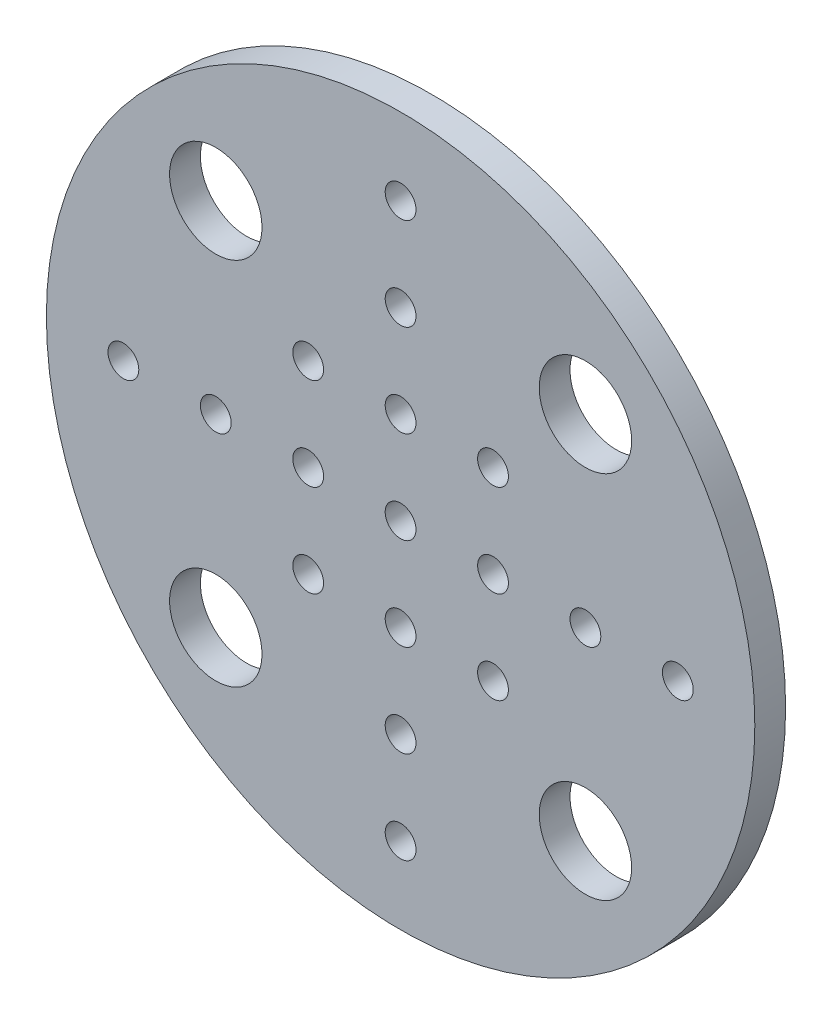
SolidWorks part; units mm, degrees
ref_plane "Alzado" through (0, 0, 0) normal (0, 0, 1) x (1, 0, 0)
ref_plane "Planta" through (0, 0, 0) normal (0, 1, 0) x (1, 0, 0)
ref_plane "Vista lateral" through (0, 0, 0) normal (1, 0, 0) x (0, 0, -1)
sketch "Model" plane through (0, 0, 0) normal (0, 0, 1) x (1, 0, 0)
  circle A0 centre (281.5188, 303.8788) radius 4.5
  circle A1 centre (281.5188, 267.8788) radius 4.5
  circle A2 centre (317.5188, 267.8788) radius 4.5
  circle A3 centre (317.5188, 303.8788) radius 4.5
  circle A4 centre (299.5188, 285.8788) radius 1.5
  circle A5 centre (299.5188, 276.8788) radius 1.5
  circle A6 centre (299.5188, 294.8788) radius 1.5
  circle A7 centre (308.5188, 285.8788) radius 1.5
  circle A8 centre (290.5188, 285.8788) radius 1.5
  circle A9 centre (299.5188, 285.8788) radius 34.5
  circle A10 centre (317.5188, 285.8788) radius 1.5
  circle A11 centre (326.5188, 285.8788) radius 1.5
  circle A12 centre (272.5188, 285.8788) radius 1.5
  circle A13 centre (281.5188, 285.8788) radius 1.5
  circle A14 centre (299.5188, 303.8788) radius 1.5
  circle A15 centre (299.5188, 312.8788) radius 1.5
  circle A16 centre (299.5188, 267.8788) radius 1.5
  circle A17 centre (299.5188, 258.8788) radius 1.5
  circle A18 centre (290.5188, 276.8788) radius 1.5
  circle A19 centre (308.5188, 294.8788) radius 1.5
  circle A20 centre (308.5188, 276.8788) radius 1.5
  circle A21 centre (290.5188, 294.8788) radius 1.5
extrude "Saliente-Extruir1" add sketch "Model" along normal blind 3
